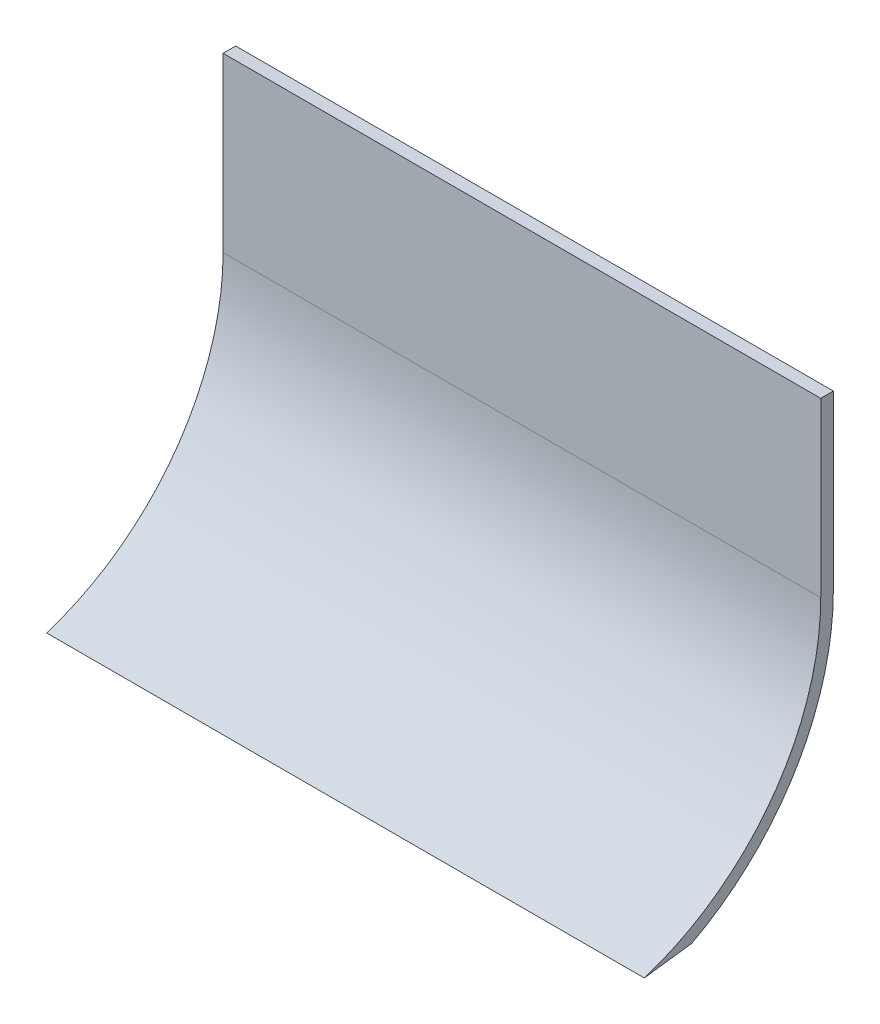
SolidWorks part; units mm, degrees
material "AISI 304"
ref_plane "Plano frontal" through (0, 0, 0) normal (0, 0, 1) x (1, 0, 0)
ref_plane "Plano superior" through (0, 0, 0) normal (0, 1, 0) x (1, 0, 0)
ref_plane "Plano direito" through (0, 0, 0) normal (1, 0, 0) x (0, 0, -1)
sketch "Esboço1" plane through (0, 0, 0) normal (1, 0, 0) x (0, 0, -1)
  line L0 (12.8149, -40.3541) -> (20.7467, -39.3113)
  line L3 (42.34, 0) -> (0, 0) construction
  line L5 (44.45, 0) -> (44.45, 28.8782)
  line L6 (44.45, 28.8782) -> (42.34, 28.8782)
  line L7 (42.34, 0) -> (42.34, 28.8782)
  arc A0 (44.45, 0) -> (20.7467, -39.3113) centre (0, 0) cw
  arc A1 (42.34, 0) -> (12.8149, -40.3541) centre (0, 0) cw
  dimension "D1" = 2.11
  dimension "D2" = 44.45
  dimension "D3" = 8
extrude "Ressalto-extrusão1" add sketch "Esboço1" along normal mid plane 100
